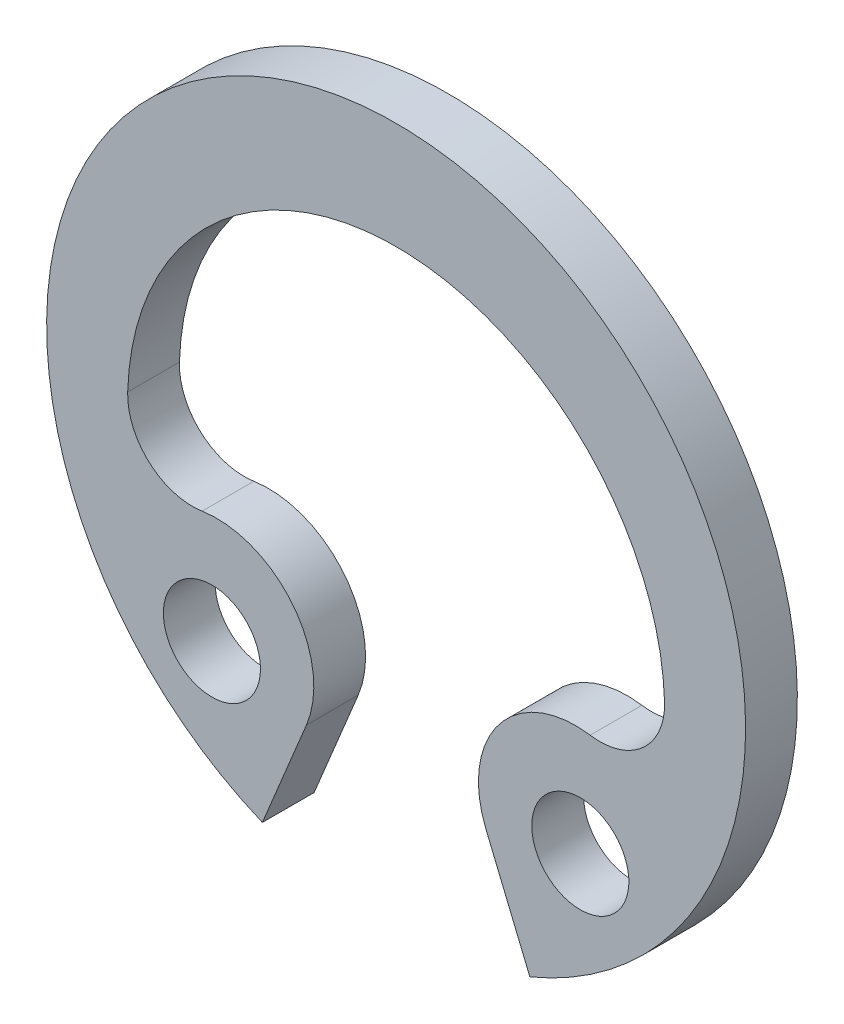
SolidWorks part; units mm, degrees
ref_plane "前视" through (0, 0, 0) normal (0, 0, 1) x (1, 0, 0)
ref_plane "上视" through (0, 0, 0) normal (0, 1, 0) x (1, 0, 0)
ref_plane "右视" through (0, 0, 0) normal (1, 0, 0) x (0, 0, -1)
sketch "尺寸草图" plane through (0, 0, 0) normal (0, 0, 1) x (1, 0, 0)
  line L0 (-5.4, 0) -> (5.4, 0) construction
  line L1 (0, 0) -> (-4.6765, -2.7) construction
  circle A0 centre (0, 0) radius 5.4
  point P5 (-2.9, 0)
  point P6 (3.1, 0)
  point P7 (1.5, 0)
  point P8 (4.1, 0)
  point P10 (-1.48, 0)
  point P11 (-0.4, 0)
  point P12 (-2.98, 0)
  point P13 (-3.7, 0)
  point P14 (34.2946, 19.8)
  dimension "DD" = 10.8
  dimension "d" = 8.3
  dimension "RR" = 4.1
  dimension "R1" = 1.5
  dimension "R2" = 1
  dimension "aa" = 45
  dimension "a" = 2.98
  dimension "d1" = 1.5
  dimension "D2" = 30
  dimension "c" = 0.4
  dimension "s" = 0.8
sketch "草图1" plane through (0, 0, 0) normal (0, 0, 1) x (1, 0, 0)
  line L0 (0, 5.4) -> (0, -4.9889) construction
  line L1 (-1.3859, -3.346) -> (-2.0665, -4.9889)
  line L2 (-2.9203, -3.1306) -> (-2.7718, -2.7719) construction
  line L3 (0, 0) -> (-2.0665, -4.9889) construction
  line L4 (1.3859, -3.346) -> (2.0665, -4.9889)
  arc A0 (2.0665, -4.9889) -> (-2.0665, -4.9889) centre (0, 0) ccw
  arc A1 (4.1479, -0.2689) -> (-4.1479, -0.2689) centre (0, -0.4) ccw
  circle A2 centre (-2.846, -2.9513) radius 0.75
  arc A3 (-1.3859, -3.346) -> (-2.9978, -1.2891) centre (-2.7718, -2.7719) ccw
  arc A4 (-2.9978, -1.2891) -> (-4.1479, -0.2689) centre (-3.1484, -0.3005) cw
  circle A5 centre (2.846, -2.9513) radius 0.75
  arc A6 (1.3859, -3.346) -> (2.9978, -1.2891) centre (2.7718, -2.7719) cw
  arc A7 (2.9978, -1.2891) -> (4.1479, -0.2689) centre (3.1484, -0.3005) ccw
  dimension "D1" = 10.8
  dimension "D2" = 8.3
  dimension "D5" = 1.5
  dimension "D7" = 1.5
  dimension "D8" = 1
  dimension "D9" = 2.98
  dimension "D3" = 0.4
  dimension "D4" = 22.5
  dimension "D6" = 4.1
extrude "基体-拉伸" add sketch "草图1" along normal blind 0.8
